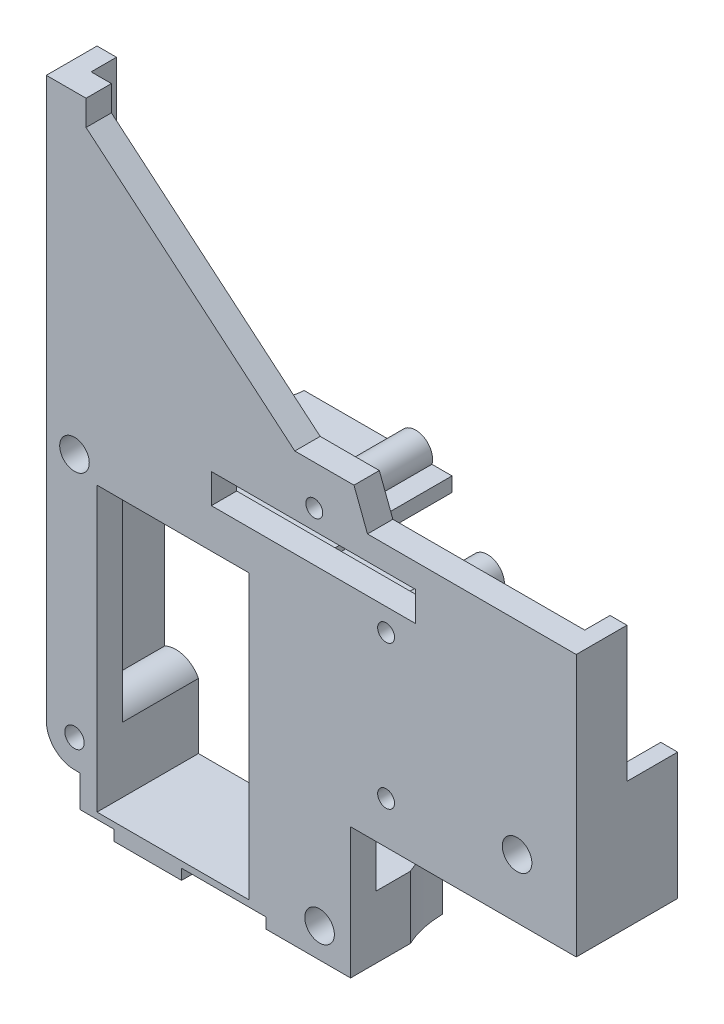
SolidWorks part; units mm, degrees
ref_plane "Plan de face" through (0, 0, 0) normal (0, 0, 1) x (1, 0, 0)
ref_plane "Plan de dessus" through (0, 0, 0) normal (0, 1, 0) x (1, 0, 0)
ref_plane "Plan de droite" through (0, 0, 0) normal (1, 0, 0) x (0, 0, -1)
sketch "Esquisse1" plane through (0, 0, 0) normal (0, 0, 1) x (1, 0, 0)
  line L0 (-11.0061, -13.4188) -> (-11.0061, 16.5812) construction
  line L1 (-12.3061, 57.5812) -> (-12.3061, 54.5812)
  line L2 (-17.0061, 57.5812) -> (-17.0061, -8.5888)
  line L3 (-9.0061, -16.9188) -> (-1.0061, -16.9188)
  line L4 (18.9939, -1.4188) -> (18.9939, -16.9188)
  line L5 (-11.0061, -13.4188) -> (6.9939, -13.4188) construction
  line L6 (6.9939, 16.5812) -> (6.9939, -13.4188) construction
  line L7 (18.9939, -1.4188) -> (45.6939, -1.4188)
  line L8 (45.6939, -1.4188) -> (45.6939, 29.5812)
  line L9 (45.6939, 29.5812) -> (20.9939, 29.5812)
  line L10 (20.9939, 29.5812) -> (19.3939, 33.7812)
  line L11 (19.3939, 33.7812) -> (12.3939, 33.7812)
  line L12 (-12.3061, 54.5812) -> (12.3939, 33.7812)
  line L13 (-13.6761, -11.9188) -> (-13.0061, -11.9188)
  line L14 (-17.0061, 57.5812) -> (-12.3061, 57.5812)
  line L15 (-13.0061, -11.9188) -> (-13.0061, -15.6688)
  line L16 (-13.0061, -15.6688) -> (-9.0061, -15.6688)
  line L17 (-9.0061, -15.6688) -> (-9.0061, -16.9188)
  line L18 (-1.0061, -16.9188) -> (-1.0061, -15.6688)
  line L19 (-1.0061, -15.6688) -> (8.9939, -15.6688)
  line L20 (8.9939, -15.6688) -> (8.9939, -16.9188)
  line L21 (8.9939, -16.9188) -> (18.9939, -16.9188)
  line L22 (6.9939, 18.5812) -> (-11.0061, 18.5812) construction
  line L23 (-4.2061, -14.9188) -> (0.1939, -14.9188) construction
  line L26 (-11.0061, -14.9188) -> (-11.0061, 18.5812)
  line L27 (6.9939, 18.5812) -> (-11.0061, 18.5812)
  line L28 (6.9939, 18.5812) -> (6.9939, -14.9188)
  line L30 (-11.0061, -14.9188) -> (6.9939, -14.9188)
  arc A0 (-17.0061, -8.5888) -> (-13.6761, -11.9188) centre (-13.6761, -8.5888) ccw
  circle A1 centre (-13.6761, -8.5888) radius 1.15
  circle A2 centre (-13.6761, 20.4112) radius 1.75
  circle A3 centre (15.3239, -13.4188) radius 1.75
  circle A4 centre (38.6939, 5.5812) radius 1.75
  circle A5 centre (23.1939, 3.5812) radius 1
  circle A6 centre (23.1939, 20.5812) radius 1
  circle A7 centre (14.6939, 29.0812) radius 1
  dimension "D19" = 6.66
  dimension "D20" = 2.3
  dimension "D21" = 3.5
  dimension "D24" = 3.5
  dimension "D26" = 3.5
  dimension "D27" = 7
  dimension "D29" = 2
  dimension "D31" = 22.5
  dimension "D32" = 2
  dimension "D34" = 2
  dimension "D1" = 6
  dimension "D2" = 3.5
  dimension "D3" = 12
  dimension "D4" = 15.5
  dimension "D5" = 26.7
  dimension "D6" = 31
  dimension "D7" = 24.7
  dimension "D8" = 4.2
  dimension "D9" = 4
  dimension "D10" = 4.7
  dimension "D11" = 3
  dimension "D12" = 29.4
  dimension "D13" = 7
  dimension "D14" = 8
  dimension "D15" = 8
  dimension "D16" = 10
  dimension "D17" = 1.25
  dimension "D18" = 5
  dimension "D22" = 29
  dimension "D23" = 29
  dimension "D25" = 3.5
  dimension "D28" = 7
  dimension "D30" = 5
  dimension "D33" = 17
  dimension "D35" = 8.5
  dimension "D36" = 8.5
extrude "Boss.-Extru.2" add sketch "Esquisse1" along normal blind 12
ref_plane "Plan1" through (0, 0, 9) normal (0, 0, 1) x (1, 0, 0)
sketch "Esquisse2" plane through (0, 0, 9) normal (0, 0, 1) x (1, 0, 0)
  line L0 (-15.0061, -5.8997) -> (-15.0061, 17.1737)
  line L1 (-17.0061, 57.5812) -> (-17.0061, -8.5888) construction
  line L2 (-11.0061, 18.5812) -> (-11.0061, -14.9188) construction
  line L3 (-11.0061, 18.1482) -> (-11.0061, -7.2209)
  line L4 (-14.7061, 24.0812) -> (-13.6761, 24.0812)
  line L5 (-10.01, 20.5812) -> (11.4939, 20.5812)
  line L7 (6.9939, 5.8812) -> (6.9939, 15.8312)
  line L8 (6.9939, -14.9188) -> (6.9939, 18.5812) construction
  line L9 (6.9939, -14.9188) -> (6.9939, 3.8812)
  line L10 (-9.0061, -16.9188) -> (-1.0061, -16.9188) construction
  line L11 (11.4939, 20.5812) -> (11.4939, 19.8312)
  line L13 (-17.0061, 57.5812) -> (-17.0061, -8.5888) construction
  line L14 (-14.7061, 24.0812) -> (-14.7061, 57.5812)
  line L15 (-12.3061, 57.5812) -> (-17.0061, 57.5812) construction
  line L16 (-12.3061, 54.5812) -> (-12.3061, 57.5812) construction
  line L17 (12.3939, 33.7812) -> (-12.3061, 54.5812) construction
  line L18 (-12.3061, 57.5812) -> (-14.7061, 57.5812)
  line L19 (-12.3061, 54.5812) -> (-12.3061, 57.5812)
  line L20 (12.3939, 33.7812) -> (-12.3061, 54.5812)
  line L21 (19.3939, 33.7812) -> (12.3939, 33.7812) construction
  line L22 (19.3939, 33.7812) -> (12.3939, 33.7812)
  line L23 (20.9939, 29.5812) -> (19.3939, 33.7812) construction
  line L24 (20.9939, 29.5812) -> (19.3939, 33.7812)
  line L25 (45.6939, 29.5812) -> (20.9939, 29.5812) construction
  line L26 (43.6939, 29.5812) -> (20.9939, 29.5812)
  line L27 (43.6939, 29.5812) -> (43.6939, 6.5812)
  line L28 (45.6939, -1.4188) -> (45.6939, 29.5812) construction
  line L29 (43.6939, 6.5812) -> (42.048, 6.5812)
  line L30 (26.6939, 6.5812) -> (26.6939, 5.8812)
  line L31 (26.6939, 5.8812) -> (6.9939, 5.8812)
  line L32 (43.6939, 4.5812) -> (42.048, 4.5812)
  line L33 (29.1939, 4.5812) -> (29.1939, 3.8812)
  line L34 (29.1939, 3.8812) -> (25.4238, 3.8812)
  line L35 (43.6939, 0.5812) -> (24.1939, 0.5812)
  line L36 (18.9939, -1.4188) -> (45.6939, -1.4188) construction
  line L37 (24.1939, 1.5656) -> (24.1939, 0.5812)
  line L38 (22.1939, 1.5656) -> (22.1939, 0.5812)
  line L39 (20.964, 3.8812) -> (6.9939, 3.8812)
  line L40 (11.4939, 15.8312) -> (6.9939, 15.8312)
  line L42 (35.3398, 6.5812) -> (26.6939, 6.5812)
  line L43 (35.3398, 4.5812) -> (29.1939, 4.5812)
  line L44 (6.9939, -14.9188) -> (9.9939, -14.9188)
  line L45 (9.9939, -14.9188) -> (9.9939, -9.5188)
  line L46 (9.9939, -9.5188) -> (18.9939, -9.5188)
  line L47 (18.9939, -16.9188) -> (18.9939, -1.4188) construction
  line L48 (8.9939, -16.9188) -> (18.9939, -16.9188) construction
  line L49 (18.9939, -9.5188) -> (18.9939, 0.5812)
  line L50 (22.1939, 0.5812) -> (18.9939, 0.5812)
  line L51 (6.9939, 5.8812) -> (6.9939, 15.8312)
  line L52 (11.4939, 19.8312) -> (21.3399, 19.8312)
  line L53 (31.4939, 19.8312) -> (31.4939, 17.8312)
  line L54 (31.4939, 17.8312) -> (11.4939, 17.8312)
  line L55 (11.4939, 17.8312) -> (11.4939, 15.8312)
  line L56 (25.048, 19.8312) -> (31.4939, 19.8312)
  line L57 (-2.0061, -13.4188) -> (-2.0061, 16.5812) construction
  line L58 (18.9939, 26.8312) -> (-2.0061, 26.8312)
  line L59 (18.9939, 26.8312) -> (18.9939, 28.5312)
  line L60 (18.9939, 28.5312) -> (16.6168, 28.5312)
  line L61 (-2.0061, 26.8312) -> (-2.0061, 28.5312)
  line L62 (12.771, 28.5312) -> (-2.0061, 28.5312)
  line L63 (43.6939, 4.5812) -> (43.6939, 0.5812)
  arc A0 (-11.0061, -7.2209) -> (-15.0061, -5.8997) centre (-13.6761, -8.5888) ccw
  arc A1 (-15.0061, 17.1737) -> (-11.0061, 18.1482) centre (-13.6761, 20.4112) ccw
  arc A2 (-10.01, 20.5812) -> (-13.6761, 24.0812) centre (-13.6761, 20.4112) ccw
  arc A3 (42.048, 6.5812) -> (35.3398, 6.5812) centre (38.6939, 5.5812) ccw
  arc A5 (25.048, 19.8312) -> (21.3399, 19.8312) centre (23.1939, 20.5812) ccw
  arc A6 (20.964, 3.8812) -> (22.1939, 1.5656) centre (23.1939, 3.5812) ccw
  arc A7 (35.3398, 4.5812) -> (42.048, 4.5812) centre (38.6939, 5.5812) ccw
  arc A8 (24.1939, 1.5656) -> (25.4238, 3.8812) centre (23.1939, 3.5812) ccw
  arc A9 (16.6168, 28.5312) -> (12.771, 28.5312) centre (14.6939, 29.0812) ccw
  dimension "D2" = 6
  dimension "D3" = 7
  dimension "D8" = 7
  dimension "D18" = 4.5
  dimension "D26" = 4
  dimension "D30" = 4
  dimension "D1" = 2
  dimension "D4" = 41
  dimension "D5" = 37.5
  dimension "D6" = 2.3
  dimension "D7" = 2
  dimension "D9" = 2
  dimension "D10" = 1
  dimension "D11" = 2
  dimension "D12" = 2
  dimension "D13" = 2.7
  dimension "D14" = 14.5
  dimension "D15" = 2.5
  dimension "D16" = 2
  dimension "D17" = 1
  dimension "D19" = 28.5
  dimension "D20" = 4.75
  dimension "D21" = 7.4
  dimension "D22" = 9
  dimension "D23" = 2
  dimension "D24" = 20
  dimension "D25" = 2
  dimension "D27" = 1.7
  dimension "D28" = 7
  dimension "D29" = 21
extrude "Enlèv. mat.-Extru.1" cut sketch "Esquisse2" against normal through all contours A5 L56 L53 L54 L55 L40 L7 L31 L30 L42 A3 L29 L27 L26 L24 L22 L20 L19 L18 L14 L4 A2 L5 L11 L52 A9 L60 L59 L58 L61 L62 | A6 L39 L9 L44 L45 L46 L49 L50 L38 | A1 L0 A0 L3 | A8 L37 L35 L63 L32 A7 L43 L33 L34
ref_plane "Plan2" through (0, 0, 6) normal (0, 0, 1) x (1, 0, 0)
sketch "Esquisse3" plane through (0, 0, 6) normal (0, 0, 1) x (1, 0, 0)
  line L0 (-14.7061, 24.0812) -> (-14.7061, 57.5812) construction
  line L1 (-17.0061, 57.5812) -> (-17.0061, -8.5888) construction
  line L2 (-14.7061, 24.0812) -> (-14.7061, 57.5812)
  line L3 (-17.0061, 57.5812) -> (-17.0061, 24.0812)
  line L4 (-14.7061, 24.0812) -> (-17.0061, 24.0812)
  line L5 (-14.7061, 57.5812) -> (-17.0061, 57.5812)
  line L6 (45.6939, 29.5812) -> (43.6939, 29.5812) construction
  line L7 (43.6939, 29.5812) -> (43.6939, 6.5812) construction
  line L8 (45.6939, -1.4188) -> (45.6939, 29.5812) construction
  line L9 (45.6939, 29.5812) -> (43.6939, 29.5812)
  line L10 (43.6939, 29.5812) -> (43.6939, 13.5812)
  line L11 (45.6939, 13.5812) -> (45.6939, 29.5812)
  line L12 (45.6939, 13.5812) -> (43.6939, 13.5812)
  dimension "D1" = 16
extrude "Enlèv. mat.-Extru.2" cut sketch "Esquisse3" against normal through all
fillet "Congé1" radius 3 1 edges at (9.9939, -9.5188, 4.5)
sketch "Esquisse4" plane through (0, 20.5812, 0) normal (0, 1, 0) x (1, 0, 0)
  circle A0 centre (-2.0061, 0) radius 2.2 construction
  circle A1 centre (-2.0061, 0) radius 2.2
extrude "Enlèv. mat.-Extru.3" cut sketch "Esquisse4" against normal up to next
sketch "Esquisse5" plane through (0, 28.5312, 0) normal (0, 1, 0) x (1, 0, 0)
  circle A0 centre (-2.0178, -0.0143) radius 3.5 construction
  circle A1 centre (-2.0178, -0.0143) radius 3.5
extrude "Enlèv. mat.-Extru.4" cut sketch "Esquisse5" against normal up to next
sketch "Esquisse6" plane through (0, 19.8312, 0) normal (0, 1, 0) x (1, 0, 0)
  arc A0 (14.9609, 3.4998) -> (14.8044, 3.4949) centre (14.9939, 0) ccw construction
  circle A1 centre (14.9939, 0) radius 3.5
extrude "Enlèv. mat.-Extru.5" cut sketch "Esquisse6" against normal blind 5
sketch "Esquisse7" plane through (0, 0, 9) normal (0, 0, -1) x (-1, 0, 0)
  line L1 (6.0979, 30.2812) -> (-1.943, 30.2812)
  line L2 (6.0979, 30.2812) -> (6.0979, 32.0812)
  line L3 (6.0979, 32.0812) -> (-1.943, 32.0812)
  line L4 (-1.943, 30.2812) -> (-1.943, 32.0812)
  line L5 (-2.5017, 31.5812) -> (-3.1893, 31.5812) construction
  line L6 (-3.1893, 30.7812) -> (-2.5017, 30.7812) construction
  dimension "D1" = 0.5
  dimension "D2" = 0.5
extrude "Enlèv. mat.-Extru.6" cut sketch "Esquisse7" against normal blind 1
sketch "Esquisse8" plane through (0, 0, 10) normal (0, 0, -1) x (-1, 0, 0)
  line L0 (-26.7441, 23.7426) -> (-3.2438, 23.7426) construction
  line L1 (-2.5188, 23.2426) -> (-26.6966, 23.2426)
  line L2 (-2.5188, 23.2426) -> (-2.5188, 26.7426)
  line L3 (-2.5188, 26.7426) -> (-26.6966, 26.7426)
  line L4 (-26.6966, 23.2426) -> (-26.6966, 26.7426)
  line L5 (-3.2438, 26.2426) -> (-26.7441, 26.2426) construction
  dimension "D1" = 0.5
  dimension "D2" = 0.5
extrude "Enlèv. mat.-Extru.7" cut sketch "Esquisse8" against normal through all and the other way blind 3
sketch "Esquisse9" plane through (0, 5.8812, 0) normal (0, 1, 0) x (1, 0, 0)
  line L0 (26.6939, 0) -> (6.9939, 0) construction
  line L1 (19.9939, 0) -> (6.9939, 0)
  line L2 (6.9939, 0) -> (6.9939, -9) construction
  line L3 (6.9939, 0) -> (6.9939, -5)
  line L4 (14.9939, -5) -> (6.9939, -5)
  arc A2 (14.9939, -5) -> (19.9939, 0) centre (14.9939, 0) ccw
  circle A3 centre (14.9939, 0) radius 1.5 construction
  dimension "D1" = 10
extrude "Enlèv. mat.-Extru.8" cut sketch "Esquisse9" against normal up to next
sketch "Esquisse10" plane through (0, 0.5812, 0) normal (0, 1, 0) x (1, 0, 0)
  circle A0 centre (29.9935, 0.1055) radius 4 construction
  circle A1 centre (29.9935, 0.1055) radius 4
extrude "Enlèv. mat.-Extru.9" cut sketch "Esquisse10" against normal up to next
sketch "Esquisse11" plane through (0, -1.4188, 0) normal (0, -1, 0) x (1, 0, 0)
  arc A3 (17.9093, 0.5118) -> (17.8939, -0.1998) centre (29.9935, -0.1055) ccw
  circle A4 centre (29.9935, -0.1055) radius 12.1
  dimension "D2" = 0.1
extrude "Enlèv. mat.-Extru.10" cut sketch "Esquisse11" along normal through all
sketch "Esquisse17" plane through (0, 26.8312, 0) normal (0, -1, 0) x (1, 0, 0)
  circle A0 centre (14.9939, 0) radius 1.5
  arc A1 (18.4939, 0) -> (11.4939, 0) centre (14.9939, 0) ccw construction
  dimension "D1" = 3
extrude "Enlèv. mat.-Extru.11" cut sketch "Esquisse17" against normal blind 1 and the other way blind 38
sketch "Esquisse18" plane through (0, 17.8312, 0) normal (0, -1, 0) x (1, 0, 0)
  line L0 (31.4939, 0) -> (18.4939, 0) construction
  circle A0 centre (23.9939, 0) radius 1.5
  dimension "D1" = 3
  dimension "D2" = 9
extrude "Enlèv. mat.-Extru.12" cut sketch "Esquisse18" against normal blind 1.2 and the other way blind 13
